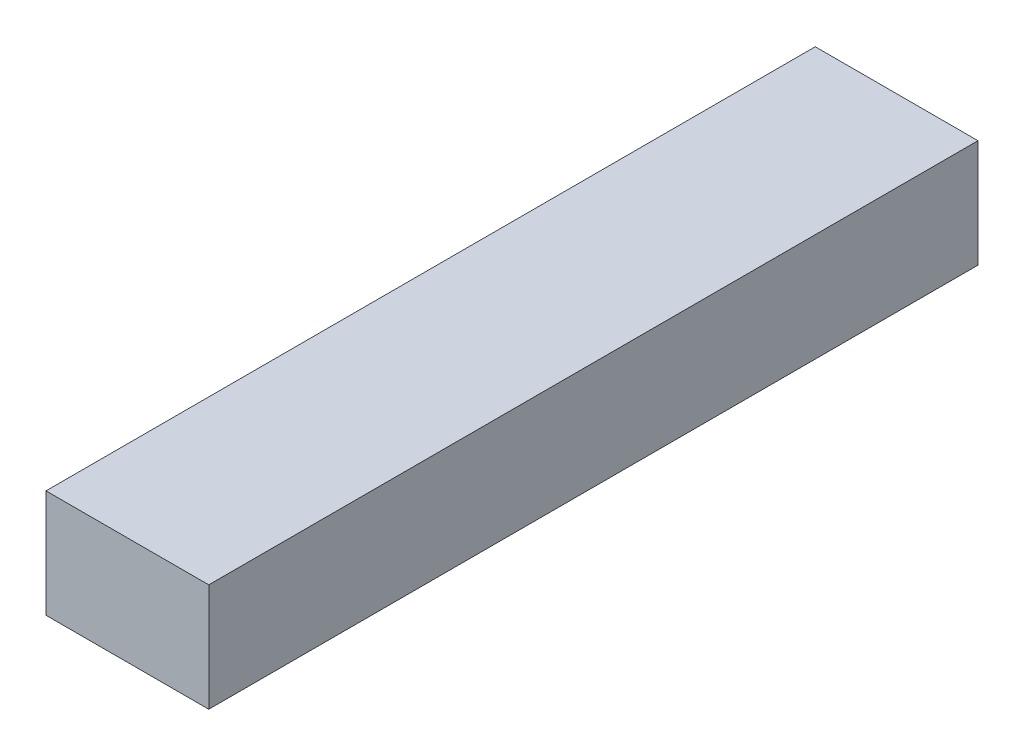
SolidWorks part; units mm, degrees
material "Polyurethane Foam Rigid"
ref_plane "Front Plane" through (0, 0, 0) normal (0, 0, 1) x (1, 0, 0)
ref_plane "Top Plane" through (0, 0, 0) normal (0, 1, 0) x (1, 0, 0)
ref_plane "Right Plane" through (0, 0, 0) normal (1, 0, 0) x (0, 0, -1)
sketch "Sketch1" plane through (0, 0, 0) normal (0, 0, 1) x (1, 0, 0)
  line L1 (-22.375, 14.815) -> (22.375, 14.815)
  line L2 (-22.375, 14.815) -> (-22.375, -14.815)
  line L3 (-22.375, -14.815) -> (22.375, -14.815)
  line L4 (22.375, 14.815) -> (22.375, -14.815)
  line L5 (-22.375, 14.815) -> (22.375, -14.815) construction
  line L6 (-22.375, -14.815) -> (22.375, 14.815) construction
  point P0 (0, 0)
  dimension "D1" = 44.75
  dimension "D2" = 29.63
extrude "Boss-Extrude1" add sketch "Sketch1" along normal blind 211.5
equation "\"D2@Sketch1\"=32.13-1.25*2"
